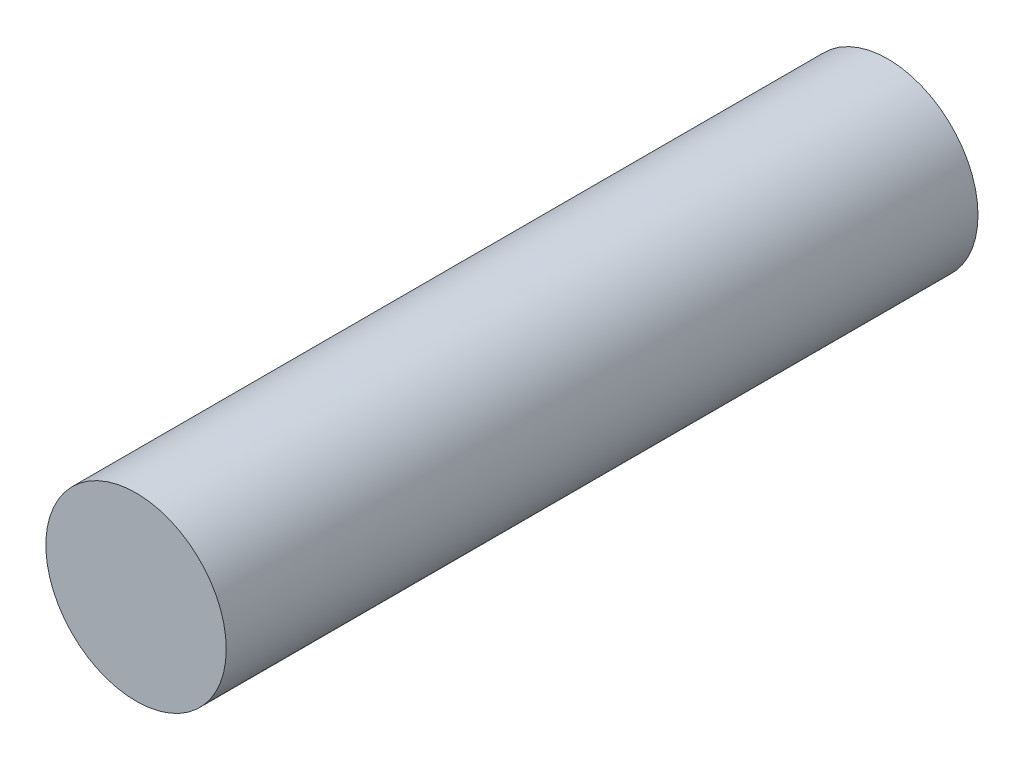
SolidWorks part; units mm, degrees
ref_plane "Front Plane" through (0, 0, 0) normal (0, 0, 1) x (1, 0, 0)
ref_plane "Top Plane" through (0, 0, 0) normal (0, 1, 0) x (1, 0, 0)
ref_plane "Right Plane" through (0, 0, 0) normal (1, 0, 0) x (0, 0, -1)
sketch "Sketch2" plane through (0, 0, 0) normal (0, 0, 1) x (1, 0, 0)
  circle A0 centre (0, 0) radius 6
extrude "Boss-Extrude1" add sketch "Sketch2" against normal mid plane 50
